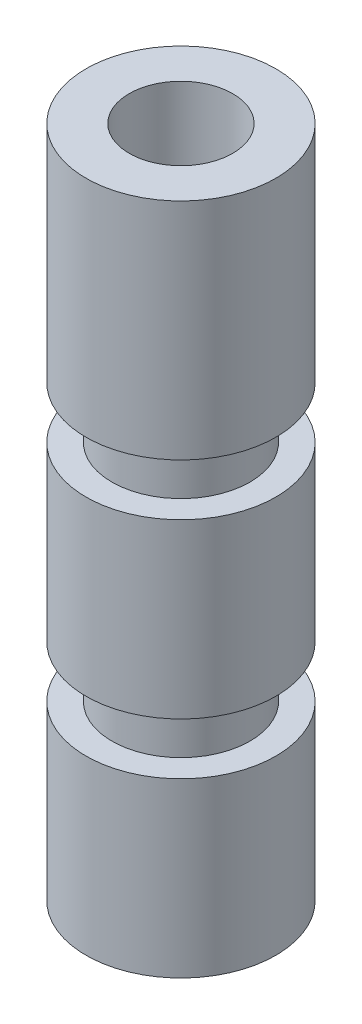
SolidWorks part; units mm, degrees
ref_plane "前视基准面" through (0, 0, 0) normal (0, 0, 1) x (1, 0, 0)
ref_plane "上视基准面" through (0, 0, 0) normal (0, 1, 0) x (1, 0, 0)
ref_plane "右视基准面" through (0, 0, 0) normal (1, 0, 0) x (0, 0, -1)
other "Configuration Table"
sketch "草图1" plane through (0, 0, 0) normal (0, 1, 0) x (1, 0, 0)
  circle A0 centre (0, 0) radius 2.75
  circle A1 centre (0, 0) radius 1.5
  dimension "D1" = 5.5
  dimension "D2" = 3
extrude "凸台-拉伸1" add sketch "草图1" along normal blind 6.5
sketch "草图2" plane through (0, 0, 0) normal (0, -1, 0) x (1, 0, 0)
  circle A0 centre (0, 0) radius 1.5
  circle A1 centre (0, 0) radius 2
  dimension "D1" = 4
extrude "凸台-拉伸2" add sketch "草图2" along normal blind 1.5
sketch "草图3" plane through (0, -1.5, 0) normal (0, -1, 0) x (1, 0, 0)
  circle A0 centre (0, 0) radius 1.5
  circle A1 centre (0, 0) radius 2.75
extrude "凸台-拉伸3" add sketch "草图3" along normal blind 5
sketch "草图4" plane through (0, -6.5, 0) normal (0, -1, 0) x (1, 0, 0)
  circle A0 centre (0, 0) radius 1.5
  circle A1 centre (0, 0) radius 2
  dimension "D1" = 4
extrude "凸台-拉伸4" add sketch "草图4" along normal blind 1.5
sketch "草图5" plane through (0, -8, 0) normal (0, -1, 0) x (1, 0, 0)
  circle A0 centre (0, 0) radius 1.5
  circle A1 centre (0, 0) radius 2.75
extrude "凸台-拉伸5" add sketch "草图5" along normal blind 5
